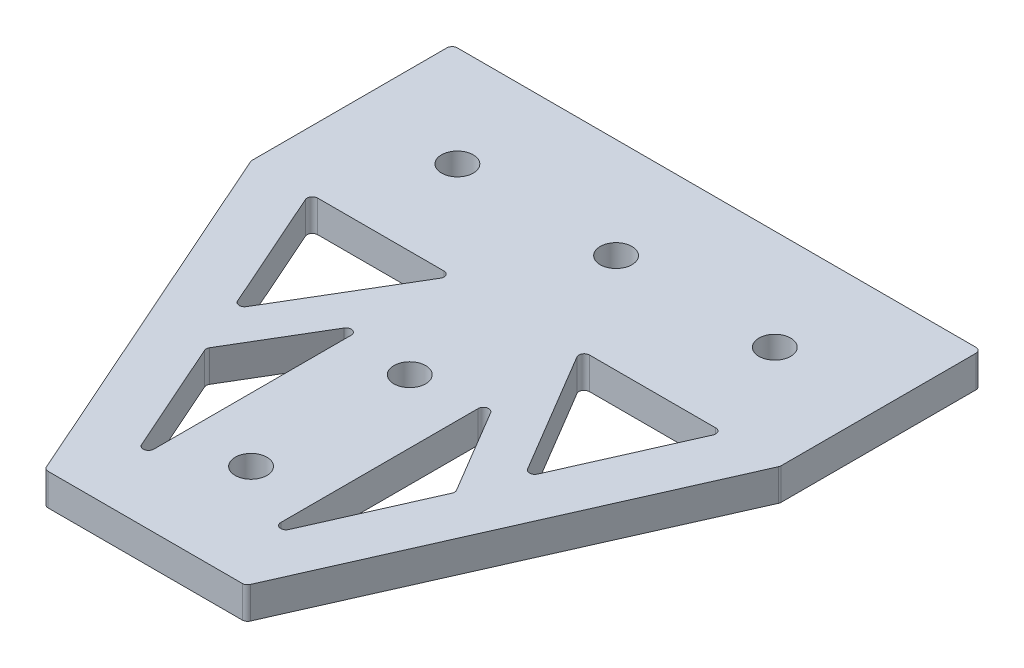
SolidWorks part; units mm, degrees
material "Thornel Mat VMA"
ref_plane "Front Plane" through (0, 0, 0) normal (0, 0, 1) x (1, 0, 0)
ref_plane "Top Plane" through (0, 0, 0) normal (0, 1, 0) x (1, 0, 0)
ref_plane "Right Plane" through (0, 0, 0) normal (1, 0, 0) x (0, 0, -1)
sketch "Sketch1" plane through (0, 0, 0) normal (0, 1, 0) x (1, 0, 0)
  line L0 (0, -9.5) -> (50, -9.5) construction
  line L3 (15.5, -54) -> (34.5, -54)
  line L6 (0, -19) -> (0, 0)
  line L7 (0, 0) -> (50, 0)
  line L8 (50, -19) -> (50, 0)
  line L9 (25, -54) -> (25, 0) construction
  line L13 (0, -19) -> (15.5, -54)
  line L14 (50, -19) -> (34.5, -54)
  circle A0 centre (10, -9.5) radius 1.5
  circle A1 centre (40, -9.5) radius 1.5
  circle A2 centre (25, -44) radius 1.5
  circle A3 centre (25, -29) radius 1.5
  circle A4 centre (25, -9.5) radius 1.5
  dimension "D6" = 10
  dimension "D8" = 3
  dimension "D11" = 10
  dimension "D12" = 10
  dimension "D13" = 10
  dimension "D14" = 15
  dimension "D4" = 15
  dimension "D5" = 15
  dimension "D1" = 19
  dimension "D2" = 54
  dimension "D3" = 19
extrude "Boss-Extrude2" add sketch "Sketch1" along normal blind 3
fillet "Fillet1" radius 0.5 6 edges at (50, 1.5, 0) (0, 1.5, 0) (50, 1.5, 19) (34.5, 1.5, 54) (15.5, 1.5, 54) (0, 1.5, 19)
sketch "Sketch2" plane through (0, 3, 0) normal (0, 1, 0) x (1, 0, 0)
  line L6 (25, -54) -> (25, 0) construction
  line L7 (15.8254, -54) -> (34.1746, -54) construction
  line L8 (49.5, 0) -> (0.5, 0) construction
  line L9 (50, -18.8942) -> (0, -18.8942) construction
  line L10 (6.1898, -18.8942) -> (18.121, -18.8942)
  line L11 (5.7326, -19.5967) -> (10.8255, -31.0967)
  line L12 (11.7124, -31.1498) -> (18.5507, -19.6498)
  line L13 (0.0428, -19.0967) -> (15.3682, -53.7025) construction
  line L14 (18.0702, -28.2841) -> (13.336, -36.2457)
  line L15 (13.3086, -36.7037) -> (18.0428, -47.3939)
  line L16 (19, -47.1915) -> (19, -28.5396)
  line L17 (38.2876, -31.1498) -> (31.4493, -19.6498)
  line L18 (31, -47.1915) -> (31, -28.5396)
  line L19 (36.6914, -36.7037) -> (31.9572, -47.3939)
  line L20 (31.9298, -28.2841) -> (36.664, -36.2457)
  line L21 (44.2674, -19.5967) -> (39.1745, -31.0967)
  line L22 (43.8102, -18.8942) -> (31.879, -18.8942)
  arc A0 (18.0428, -47.3939) -> (19, -47.1915) centre (18.5, -47.1915) ccw
  arc A1 (13.336, -36.2457) -> (13.3086, -36.7037) centre (13.7657, -36.5012) ccw
  arc A2 (18.0702, -28.2841) -> (19, -28.5396) centre (18.5, -28.5396) cw
  arc A3 (18.121, -18.8942) -> (18.5507, -19.6498) centre (18.121, -19.3942) cw
  arc A4 (10.8255, -31.0967) -> (11.7124, -31.1498) centre (11.2827, -30.8942) ccw
  arc A5 (6.1898, -18.8942) -> (5.7326, -19.5967) centre (6.1898, -19.3942) ccw
  arc A6 (39.1745, -31.0967) -> (38.2876, -31.1498) centre (38.7173, -30.8942) cw
  arc A7 (31.9298, -28.2841) -> (31, -28.5396) centre (31.5, -28.5396) ccw
  arc A8 (36.664, -36.2457) -> (36.6914, -36.7037) centre (36.2343, -36.5012) cw
  arc A9 (31.9572, -47.3939) -> (31, -47.1915) centre (31.5, -47.1915) cw
  arc A10 (43.8102, -18.8942) -> (44.2674, -19.5967) centre (43.8102, -19.3942) cw
  arc A11 (31.879, -18.8942) -> (31.4493, -19.6498) centre (31.879, -19.3942) ccw
  point P32 (19, -18.8942)
  dimension "D7" = 0.5
  dimension "D1" = 0
  dimension "D2" = 5
  dimension "D3" = 6
  dimension "D4" = 5
  dimension "D5" = 4
  dimension "D6" = 6
  dimension "D8" = 12
extrude "Cut-Extrude1" cut sketch "Sketch2" against normal blind 3
